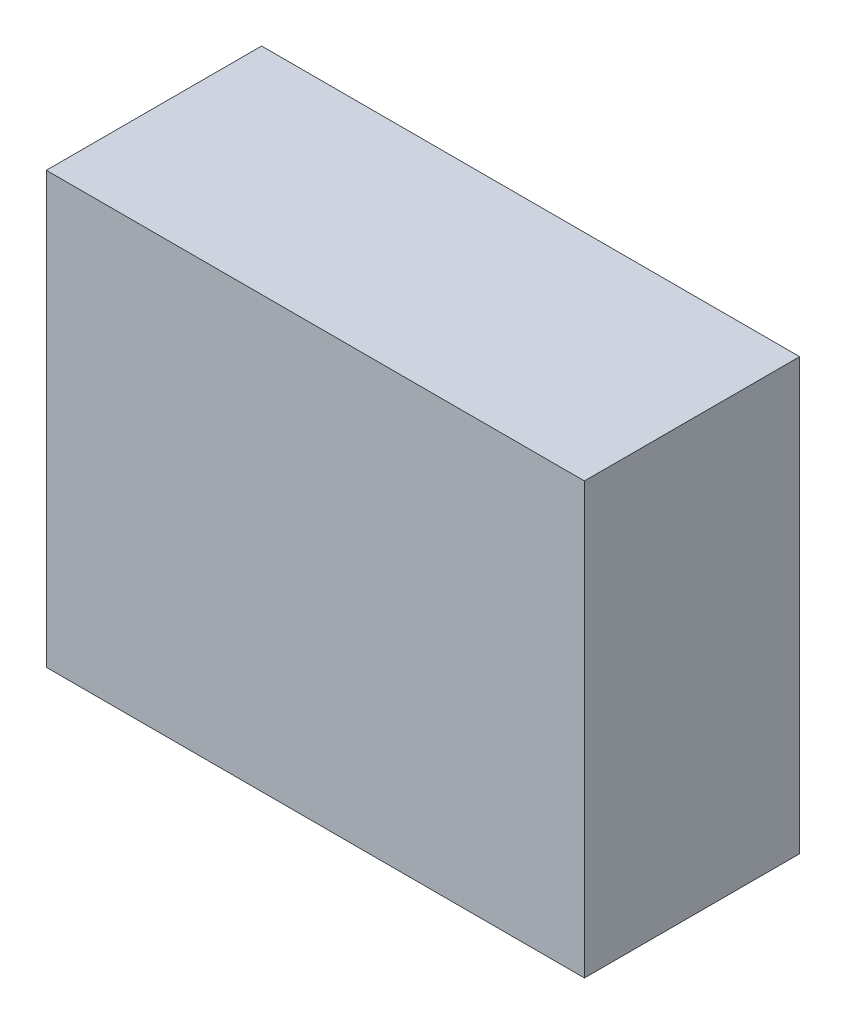
SolidWorks part; units mm, degrees
ref_plane "Plano frontal" through (0, 0, 0) normal (0, 0, 1) x (1, 0, 0)
ref_plane "Plano superior" through (0, 0, 0) normal (0, 1, 0) x (1, 0, 0)
ref_plane "Plano direito" through (0, 0, 0) normal (1, 0, 0) x (0, 0, -1)
sketch "Esboço1" plane through (0, 0, 0) normal (0, 1, 0) x (1, 0, 0)
  line L1 (-25, -10) -> (25, -10)
  line L2 (-25, -10) -> (-25, 10)
  line L3 (-25, 10) -> (25, 10)
  line L4 (25, -10) -> (25, 10)
  line L5 (-25, -10) -> (25, 10) construction
  line L6 (-25, 10) -> (25, -10) construction
  point P0 (0, 0)
  dimension "D1" = 50
  dimension "D2" = 20
extrude "Ressalto-extrusão1" add sketch "Esboço1" along normal blind 40
